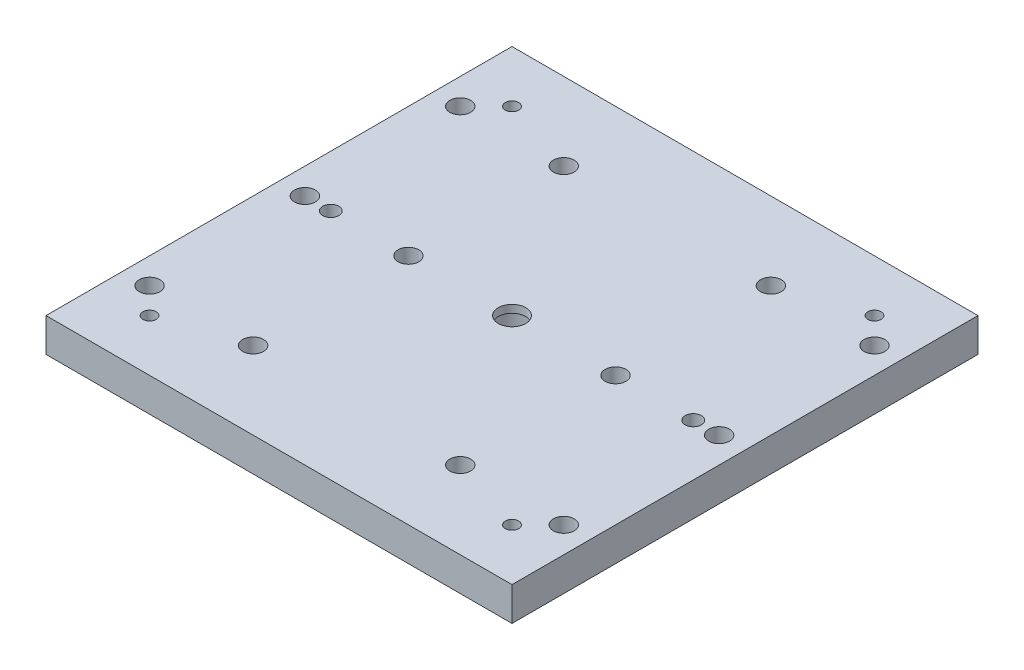
SolidWorks part; units mm, degrees
material "6061-T6 (SS)"
ref_plane "Front Plane" through (0, 0, 0) normal (0, 0, 1) x (1, 0, 0)
ref_plane "Top Plane" through (0, 0, 0) normal (0, 1, 0) x (1, 0, 0)
ref_plane "Right Plane" through (0, 0, 0) normal (1, 0, 0) x (0, 0, -1)
sketch "Sketch1" plane through (0, 0, 0) normal (0, 1, 0) x (1, 0, 0)
  line L1 (-57.15, 57.15) -> (57.15, 57.15)
  line L2 (-57.15, 57.15) -> (-57.15, -57.15)
  line L3 (-57.15, -57.15) -> (57.15, -57.15)
  line L4 (57.15, 57.15) -> (57.15, -57.15)
  line L5 (-57.15, 57.15) -> (57.15, -57.15) construction
  line L6 (-57.15, -57.15) -> (57.15, 57.15) construction
  point P0 (0, 0)
  dimension "D1" = 114.3
  dimension "D2" = 114.3
extrude "stock" add sketch "Sketch1" along normal blind 8.255
hole_wizard "CBORE for 1/4 Socket Head Cap Screw1" positions "Sketch2" profile "Sketch3" counterbore size "1/4" standard "ANSI Inch" end condition up to next
sketch "Sketch2" plane through (0, 0, 0) normal (0, -1, 0) x (-1, 0, 0)
  point P0 (0, 0)
sketch "Sketch3" plane through (0, 0, 0) normal (1, 0, 0) x (0, 0, -1)
  line L0 (0, 0) -> (0, 8.255)
  line L1 (0, 8.255) -> (3.3782, 8.255)
  line L3 (3.3782, 8.255) -> (3.3782, 6.35)
  line L4 (3.3782, 6.35) -> (5.5562, 6.35)
  line L5 (5.5562, 6.35) -> (5.5562, 0)
  line L7 (5.5562, 0) -> (0, 0)
  line L11 (0, -6.35) -> (0, 107.95) construction
  dimension "Thru Hole Dia." = 6.7564
  dimension "Thru Hole Depth" = 8.255
  dimension "C'Bore Dia." = 11.1125
  dimension "C'Bore Depth" = 6.35
hole_wizard "5/32 (0.15625) Diameter Hole1" positions "Sketch4" profile "Sketch5" hole size "5/32" standard "ANSI Inch" end condition up to next
sketch "Sketch4" plane through (0, 8.255, 0) normal (0, 1, 0) x (1, 0, 0)
  line L0 (44.45, 0) -> (-44.45, 0) construction
  circle A0 centre (0, 0) radius 3.3782 construction
  point P0 (44.45, 0)
  point P2 (-44.45, 0)
  point P8 (0, 0)
  dimension "D1" = 88.9
sketch "Sketch5" plane through (44.45, 8.255, 0) normal (1, 0, 0) x (0, 0, 1)
  line L0 (0, 0) -> (0, 8.255)
  line L1 (0, 8.255) -> (1.9844, 8.255)
  line L2 (1.9844, 8.255) -> (1.9844, 0)
  line L5 (1.9844, 0) -> (0, 0)
  line L11 (0, -6.35) -> (0, 107.95) construction
  dimension "Thru Hole Dia." = 3.9688
  dimension "Thru Hole Depth" = 8.255
hole_wizard "CBORE for #4 Socket Head Cap Screw1" positions "Sketch6" profile "Sketch7" counterbore size "#4" standard "ANSI Inch" end condition up to next
sketch "Sketch6" plane through (0, 0, 0) normal (0, -1, 0) x (-1, 0, 0)
  line L1 (44.45, -44.45) -> (-44.45, -44.45)
  line L2 (44.45, -44.45) -> (44.45, 44.45)
  line L3 (44.45, 44.45) -> (-44.45, 44.45)
  line L4 (-44.45, -44.45) -> (-44.45, 44.45)
  line L5 (44.45, -44.45) -> (-44.45, 44.45) construction
  line L6 (44.45, 44.45) -> (-44.45, -44.45) construction
  point P0 (44.45, -44.45)
  point P2 (44.45, 44.45)
  point P4 (-44.45, 44.45)
  point P6 (-44.45, -44.45)
  point P8 (0, 0)
  dimension "D1" = 88.9
sketch "Sketch7" plane through (-44.45, 0, 44.45) normal (1, 0, 0) x (0, 0, -1)
  line L0 (0, 0) -> (0, 8.255)
  line L1 (0, 8.255) -> (1.6319, 8.255)
  line L3 (1.6319, 8.255) -> (1.632, 2.8448)
  line L4 (1.632, 2.8448) -> (2.7788, 2.8448)
  line L5 (2.7788, 2.8448) -> (2.7788, 0)
  line L7 (2.7788, 0) -> (0, 0)
  line L11 (0, -6.35) -> (0, 107.95) construction
  dimension "Thru Hole Dia." = 3.2639
  dimension "Thru Hole Depth" = 8.255
  dimension "C'Bore Dia." = 5.5575
  dimension "C'Bore Depth" = 2.8448
hole_wizard "1/4-20 Tapped Hole1" positions "Sketch8" profile "Sketch9" tap size "1/4-20" standard "ANSI Inch" end condition up to next
sketch "Sketch8" plane through (0, 0, 0) normal (0, -1, 0) x (-1, 0, 0)
  line L0 (25.4, 0) -> (50.8, 0) construction
  line L1 (50.8, 0) -> (50.8, -38.1) construction
  line L2 (25.4, -38.1) -> (25.4, 0) construction
  line L3 (25.4, 0) -> (25.4, 38.1) construction
  line L4 (50.8, 0) -> (50.8, 38.1) construction
  line L5 (-25.4, -38.1) -> (-25.4, 0) construction
  line L6 (-25.4, 0) -> (-25.4, 38.1) construction
  line L8 (-50.8, 0) -> (-25.4, 0) construction
  line L9 (-50.8, 0) -> (-50.8, -38.1) construction
  line L10 (-50.8, 0) -> (-50.8, 38.1) construction
  line L11 (-25.4, 0) -> (25.4, 0) construction
  point P0 (50.8, -38.1)
  point P2 (25.4, -38.1)
  point P4 (25.4, 0)
  point P6 (50.8, 0)
  point P8 (50.8, 38.1)
  point P10 (25.4, 38.1)
  point P26 (-25.4, 38.1)
  point P28 (-50.8, 38.1)
  point P30 (-50.8, 0)
  point P32 (-25.4, 0)
  point P34 (-25.4, -38.1)
  point P36 (-50.8, -38.1)
  point P59 (0, 0)
  point P63 (-38.1, 0)
  point P64 (38.1, 0)
  dimension "D1" = 76.2
  dimension "D2" = 38.1
  dimension "D3" = 25.4
sketch "Sketch9" plane through (-50.8, 0, 38.1) normal (1, 0, 0) x (0, 0, -1)
  line L0 (0, 0) -> (0, 8.255)
  line L1 (0, 8.255) -> (2.5527, 8.255)
  line L2 (2.5527, 8.255) -> (2.5527, 0)
  line L5 (2.5527, 0) -> (0, 0)
  line L11 (0, -6.35) -> (0, 107.95) construction
  dimension "Thru Tap Drill Dia." = 5.1054
  dimension "Thru Tap Drill Depth" = 8.255
cosmetic thread "Hole Thread1" parameters "D2"=6.35
cosmetic thread "Hole Thread2" parameters "D2"=6.35
cosmetic thread "Hole Thread3" parameters "D2"=6.35
cosmetic thread "Hole Thread4" parameters "D2"=6.35
cosmetic thread "Hole Thread5" parameters "D2"=6.35
cosmetic thread "Hole Thread6" parameters "D2"=6.35
cosmetic thread "Hole Thread7" parameters "D2"=6.35
cosmetic thread "Hole Thread8" parameters "D2"=6.35
cosmetic thread "Hole Thread9" parameters "D2"=6.35
cosmetic thread "Hole Thread10" parameters "D2"=6.35
cosmetic thread "Hole Thread11" parameters "D2"=6.35
cosmetic thread "Hole Thread12" parameters "D2"=6.35
sketch "Sketch10" plane through (0, 0, 0) normal (0, -1, 0) x (1, 0, 0)
  line L4 (57.15, -57.15) -> (57.15, 57.15)
  line L5 (57.15, 57.15) -> (-57.15, 57.15)
  line L6 (-57.15, 57.15) -> (-57.15, -57.15)
  line L7 (-57.15, -57.15) -> (57.15, -57.15)
  line L8 (57.15, -57.15) -> (57.15, 57.15)
  line L9 (57.15, 57.15) -> (-57.15, 57.15)
  line L10 (-57.15, 57.15) -> (-57.15, -57.15)
  line L11 (-57.15, -57.15) -> (57.15, -57.15)
  circle A0 centre (-50.8, 38.1) radius 2.5527 construction
  circle A1 centre (-25.4, 38.1) radius 2.5527 construction
  circle A2 centre (-50.8, 0) radius 2.5527 construction
  circle A3 centre (-25.4, 0) radius 2.5527 construction
  circle A4 centre (-50.8, -38.1) radius 2.5527 construction
  circle A5 centre (-25.4, -38.1) radius 2.5527 construction
  circle A6 centre (25.4, 38.1) radius 2.5527 construction
  circle A7 centre (50.8, 38.1) radius 2.5527 construction
  circle A8 centre (25.4, 0) radius 2.5527 construction
  circle A9 centre (50.8, 0) radius 2.5527 construction
  circle A10 centre (25.4, -38.1) radius 2.5527 construction
  circle A11 centre (50.8, -38.1) radius 2.5527 construction
  circle A12 centre (-50.8, 38.1) radius 2.5527
  circle A13 centre (-25.4, 38.1) radius 2.5527
  circle A14 centre (-50.8, 0) radius 2.5527
  circle A15 centre (-25.4, 0) radius 2.5527
  circle A16 centre (-50.8, -38.1) radius 2.5527
  circle A17 centre (-25.4, -38.1) radius 2.5527
  circle A18 centre (25.4, 38.1) radius 2.5527
  circle A19 centre (50.8, 38.1) radius 2.5527
  circle A20 centre (25.4, 0) radius 2.5527
  circle A21 centre (50.8, 0) radius 2.5527
  circle A22 centre (25.4, -38.1) radius 2.5527
  circle A23 centre (50.8, -38.1) radius 2.5527
  dimension "D1" = 0
